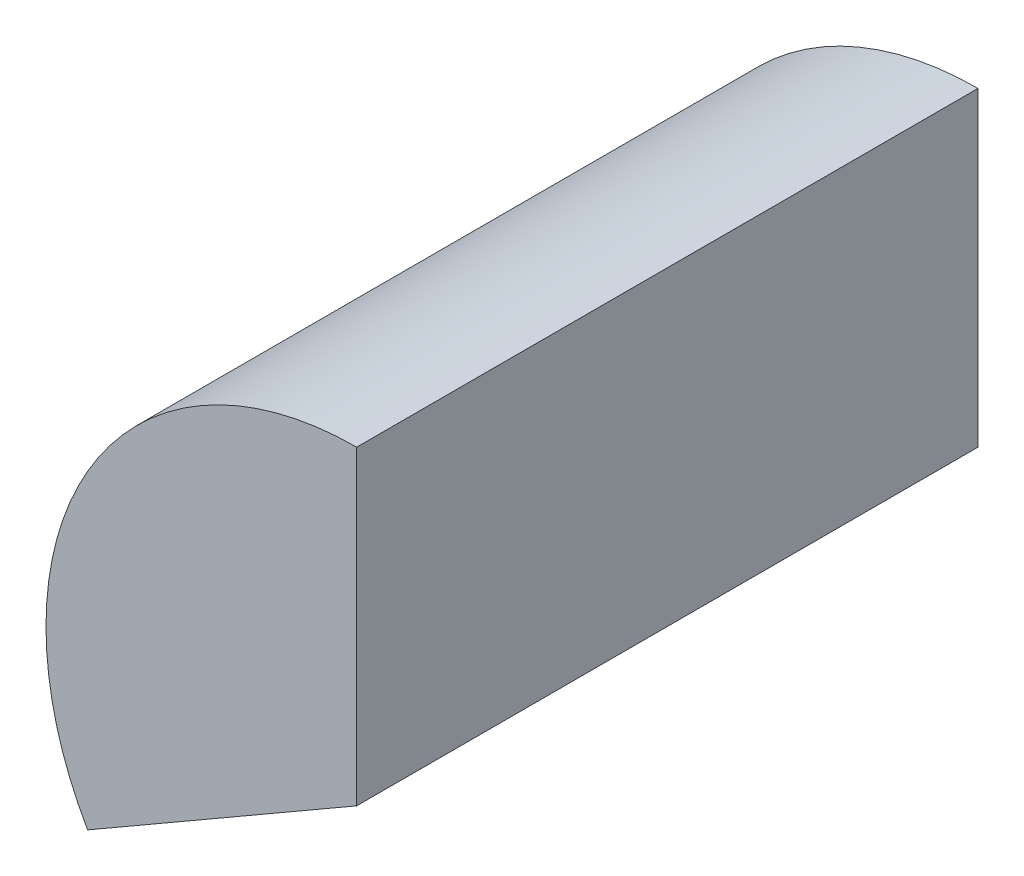
SolidWorks part; units mm, degrees
ref_plane "Alzado" through (0, 0, 0) normal (0, 0, 1) x (1, 0, 0)
ref_plane "Planta" through (0, 0, 0) normal (0, 1, 0) x (1, 0, 0)
ref_plane "Vista lateral" through (0, 0, 0) normal (1, 0, 0) x (0, 0, -1)
sketch "Croquis1" plane through (0, 0, 0) normal (0, 0, 1) x (1, 0, 0)
  line L0 (0, 25) -> (0, 0)
  line L1 (0, 0) -> (-21.6506, -12.5)
  arc A0 (0, 25) -> (-21.6506, -12.5) centre (0, 0) ccw
  dimension "D1" = 50
  dimension "D2" = 120
extrude "Saliente-Extruir1" add sketch "Croquis1" along normal blind 50
sketch "Croquis2" plane through (0, 0, 0) normal (0, 0, -1) x (-1, 0, 0)
  circle A0 centre (11.4408, 7.2486) radius 5
  dimension "D1" = 10
extrude "Cortar-Extruir1" cut sketch "Croquis2" against normal blind 10
